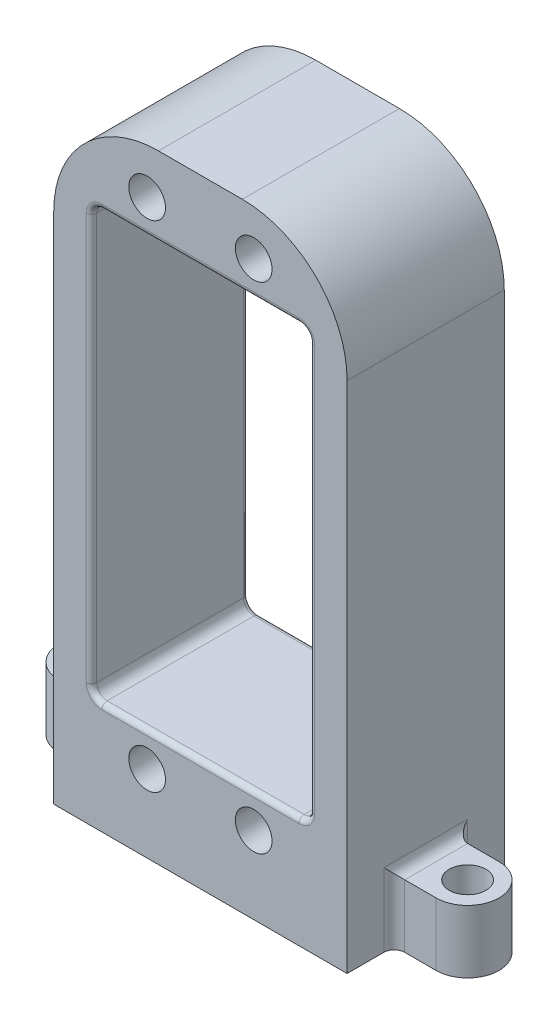
SolidWorks part; units mm, degrees
ref_plane "Front Plane" through (0, 0, 0) normal (0, 0, 1) x (1, 0, 0)
ref_plane "Top Plane" through (0, 0, 0) normal (0, 1, 0) x (1, 0, 0)
ref_plane "Right Plane" through (0, 0, 0) normal (1, 0, 0) x (0, 0, -1)
sketch "Sketch1" plane through (0, 0, 0) normal (0, 0, 1) x (1, 0, 0)
  line L1 (-5.085, -23.63) -> (5.085, -23.63) construction
  line L2 (-5.085, -23.63) -> (-5.085, 23.63) construction
  line L3 (-5.085, 23.63) -> (5.085, 23.63) construction
  line L4 (5.085, -23.63) -> (5.085, 23.63) construction
  line L5 (-5.085, -23.63) -> (5.085, 23.63) construction
  line L6 (-5.085, 23.63) -> (5.085, -23.63) construction
  line L7 (-10.4, -20.4) -> (10.4, -20.4)
  line L8 (-10.4, -20.4) -> (-10.4, 20.4)
  line L9 (-10.4, 20.4) -> (10.4, 20.4)
  line L10 (10.4, -20.4) -> (10.4, 20.4)
  line L11 (-10.4, -20.4) -> (10.4, 20.4) construction
  line L12 (-10.4, 20.4) -> (10.4, -20.4) construction
  line L13 (-14, -28) -> (14, -28)
  line L14 (-14, -28) -> (-14, 28)
  line L15 (-14, 28) -> (14, 28)
  line L16 (14, -28) -> (14, 28)
  line L17 (-14, -28) -> (14, 28) construction
  line L18 (-14, 28) -> (14, -28) construction
  circle A0 centre (-5.085, 23.63) radius 1.75
  circle A1 centre (5.085, 23.63) radius 1.75
  circle A2 centre (-5.085, -23.63) radius 1.75
  circle A3 centre (5.085, -23.63) radius 1.75
  point P0 (0, 0)
  point P10 (0, 0)
  point P15 (0, 0)
  dimension "D3" = 3.5
  dimension "D1" = 10.17
  dimension "D2" = 47.26
  dimension "D4" = 20.8
  dimension "D5" = 40.8
  dimension "D6" = 28
  dimension "D7" = 56
extrude "Boss-Extrude1" add sketch "Sketch1" along normal blind 15
fillet "Fillet1" radius 10 2 edges at (14, 28, 7.5) (-14, 28, 7.5)
fillet "Fillet2" radius 1 4 edges at (10.4, -20.4, 7.5) (-10.4, -20.4, 7.5) (-10.4, 20.4, 7.5) (10.4, 20.4, 7.5)
fillet "Fillet3" radius 0.5 16 edges at (10.1071, -20.1071, 0) (-10.1071, -20.1071, 0) (-10.1071, 20.1071, 0) (10.1071, 20.1071, 0) (10.1071, -20.1071, 15) (-10.1071, -20.1071, 15) (-10.1071, 20.1071, 15) (10.1071, 20.1071, 15) (0, -20.4, 0) (-10.4, 0, 0) (0, 20.4, 0) (10.4, 0, 0) (0, 20.4, 15) (-10.4, 0, 15) (0, -20.4, 15) (10.4, 0, 15)
sketch "Sketch2" plane through (0, -28, 0) normal (0, -1, 0) x (1, 0, 0)
  line L0 (14, 15) -> (14, 0) construction
  line L1 (18, 4.5) -> (14, 4.5)
  line L2 (14, 4.5) -> (14, 10.5)
  line L3 (14, 10.5) -> (18, 10.5)
  line L4 (0, -8.25) -> (0, 8.25) construction
  line L5 (-14, 4.5) -> (-14, 10.5)
  line L6 (-14, 10.5) -> (-18, 10.5)
  line L7 (-18, 4.5) -> (-14, 4.5)
  line L8 (-18, 7.5) -> (18, 7.5) construction
  line L9 (0, 15) -> (0, 0) construction
  line L10 (-14, 15) -> (14, 15) construction
  circle A0 centre (18, 7.5) radius 1.75
  circle A1 centre (18, 7.5) radius 3
  circle A2 centre (-18, 7.5) radius 3
  circle A3 centre (-18, 7.5) radius 1.75
  point P23 (0, 7.5)
  point P24 (0, 7.5)
  line M6 (14, 0) -> (14, 15)
  line M8 (-14, 15) -> (-14, 0)
  dimension "D1" = 3.5
  dimension "D2" = 6
  dimension "D3" = 4
extrude "Boss-Extrude2" add sketch "Sketch2" against normal blind 3 contours A2 A3 | L6 A2 L7 M8 | A1 L3 L1 M6 | A1 A0
fillet "Fillet4" radius 1 2 edges at (-14, -25, 7.5) (14, -25, 7.5)
fillet "Fillet5" radius 1 4 edges at (14, -26, 10.5) (14, -26, 4.5) (-14, -26, 4.5) (-14, -26, 10.5)
sketch "Sketch3" plane through (0, -28, 0) normal (0, -1, 0) x (1, 0, 0)
  line L10 (-14, 0) -> (14, 0)
  line L11 (14, 0) -> (14, 3.5)
  line L12 (15, 4.5) -> (18, 4.5)
  line L13 (18, 10.5) -> (15, 10.5)
  line L14 (14, 11.5) -> (14, 15)
  line L15 (14, 15) -> (-14, 15)
  line L16 (-14, 15) -> (-14, 11.5)
  line L17 (-15, 10.5) -> (-18, 10.5)
  line L18 (-18, 4.5) -> (-15, 4.5)
  line L19 (-14, 3.5) -> (-14, 0)
  line L20 (-14, 0) -> (14, 0)
  line L21 (14, 0) -> (14, 3.5)
  line L22 (15, 4.5) -> (18, 4.5)
  line L23 (18, 10.5) -> (15, 10.5)
  line L24 (14, 11.5) -> (14, 15)
  line L25 (14, 15) -> (-14, 15)
  line L26 (-14, 15) -> (-14, 11.5)
  line L27 (-15, 10.5) -> (-18, 10.5)
  line L28 (-18, 4.5) -> (-15, 4.5)
  line L29 (-14, 3.5) -> (-14, 0)
  circle A0 centre (18, 7.5) radius 1.75 construction
  circle A1 centre (-18, 7.5) radius 1.75 construction
  circle A2 centre (18, 7.5) radius 1.75
  circle A3 centre (-18, 7.5) radius 1.75
  arc A6 (15, 4.5) -> (14, 3.5) centre (15, 3.5) ccw
  arc A7 (18, 4.5) -> (18, 10.5) centre (18, 7.5) ccw
  arc A8 (14, 11.5) -> (15, 10.5) centre (15, 11.5) ccw
  arc A9 (-15, 10.5) -> (-14, 11.5) centre (-15, 11.5) ccw
  arc A10 (-18, 10.5) -> (-18, 4.5) centre (-18, 7.5) ccw
  arc A11 (-14, 3.5) -> (-15, 4.5) centre (-15, 3.5) ccw
  arc A12 (15, 4.5) -> (14, 3.5) centre (15, 3.5) ccw
  arc A13 (18, 4.5) -> (18, 10.5) centre (18, 7.5) ccw
  arc A14 (14, 11.5) -> (15, 10.5) centre (15, 11.5) ccw
  arc A15 (-15, 10.5) -> (-14, 11.5) centre (-15, 11.5) ccw
  arc A16 (-18, 10.5) -> (-18, 4.5) centre (-18, 7.5) ccw
  arc A17 (-14, 3.5) -> (-15, 4.5) centre (-15, 3.5) ccw
  dimension "D1" = 0
extrude "Boss-Extrude3" add sketch "Sketch3" along normal blind 3
